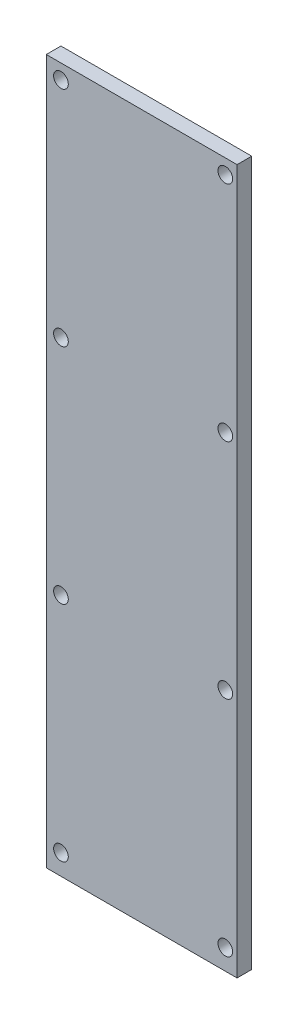
SolidWorks part; units mm, degrees
ref_plane "Front Plane" through (0, 0, 0) normal (0, 0, 1) x (1, 0, 0)
ref_plane "Top Plane" through (0, 0, 0) normal (0, 1, 0) x (1, 0, 0)
ref_plane "Right Plane" through (0, 0, 0) normal (1, 0, 0) x (0, 0, -1)
sketch "Sketch1" plane through (0, 0, 0) normal (0, 1, 0) x (1, 0, 0)
  line L1 (-48.3681, 30.6016) -> (34.1819, 30.6016)
  line L2 (-48.3681, 30.6016) -> (-48.3681, 24.2516)
  line L3 (-48.3681, 24.2516) -> (34.1819, 24.2516)
  line L4 (34.1819, 30.6016) -> (34.1819, 24.2516)
  dimension "D1" = 6.35
  dimension "D2" = 82.55
extrude "Boss-Extrude1" add sketch "Sketch1" along normal blind 304.8
sketch "Sketch2" plane through (0, 0, -24.2516) normal (0, 0, 1) x (1, 0, 0)
  line L0 (-48.3681, 304.8) -> (-48.3681, 0) construction
  line L1 (-48.3681, 304.8) -> (34.1819, 304.8) construction
  circle A0 centre (-42.0181, 298.45) radius 3.175
  dimension "D1" = 6.35
  dimension "D2" = 6.35
  dimension "D3" = 6.35
extrude "Cut-Extrude1" cut sketch "Sketch2" against normal blind 152.4
pattern_linear "LPattern1" count 4 spacing 96.52 along (0, -1, 0) of "Cut-Extrude1"
pattern_linear "LPattern2" count 2 spacing 71.12 along (1, 0, 0) of "LPattern1", "Cut-Extrude1"
